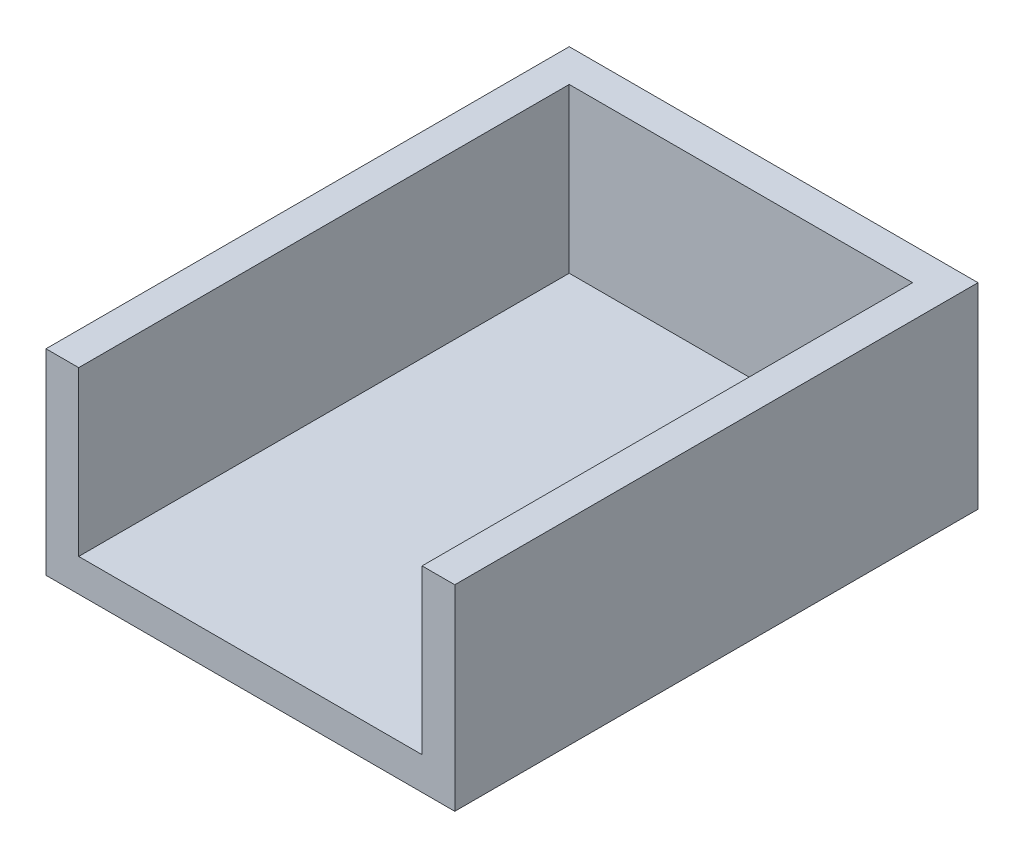
SolidWorks part; units mm, degrees
ref_plane "Front Plane" through (0, 0, 0) normal (0, 0, 1) x (1, 0, 0)
ref_plane "Top Plane" through (0, 0, 0) normal (0, 1, 0) x (1, 0, 0)
ref_plane "Right Plane" through (0, 0, 0) normal (1, 0, 0) x (0, 0, -1)
sketch "Sketch1" plane through (0, 0, 0) normal (0, 1, 0) x (1, 0, 0)
  line L1 (-62.5, -80) -> (62.5, -80)
  line L2 (-62.5, -80) -> (-62.5, 80)
  line L3 (-62.5, 80) -> (62.5, 80)
  line L4 (62.5, -80) -> (62.5, 80)
  line L5 (-62.5, -80) -> (62.5, 80) construction
  line L6 (-62.5, 80) -> (62.5, -80) construction
  point P0 (0, 0)
  dimension "D1" = 160
  dimension "D2" = 125
extrude "Boss-Extrude1" add sketch "Sketch1" along normal blind 60
shell "Shell1" thickness 10
sketch "Sketch2" plane through (0, 0, -80) normal (0, 0, -1) x (-1, 0, 0)
  line L0 (65.75, 53) -> (65.75, 3) construction
  line L1 (58.1499, 28.0001) -> (-53.2501, 28.0001)
  line L5 (65.75, 53) -> (65.75, 3) construction
  line L6 (-53.2501, 16.0001) -> (58.1499, 16.0001)
  line L7 (62.8337, 23.7501) -> (53.4662, 23.7501)
  line L8 (62.8337, 23.7501) -> (53.4662, 23.7501) construction
  line L9 (-48.5663, 23.7501) -> (-57.9338, 23.7501)
  line L10 (-48.5663, 23.7501) -> (-57.9338, 23.7501) construction
  arc A0 (53.4662, 23.7501) -> (62.8337, 23.7501) centre (58.1499, 22.0001) ccw
  arc A1 (53.4662, 23.7501) -> (62.8337, 23.7501) centre (58.1499, 22.0001) ccw construction
  arc A2 (-57.9338, 23.7501) -> (-48.5663, 23.7501) centre (-53.2501, 22.0001) ccw
  arc A3 (-57.9338, 23.7501) -> (-48.5663, 23.7501) centre (-53.2501, 22.0001) ccw construction
  arc A4 (-53.2501, 28.0001) -> (-53.2501, 16.0001) centre (-53.2501, 22.0001) ccw
  arc A5 (58.1499, 16.0001) -> (58.1499, 28.0001) centre (58.1499, 22.0001) ccw
  point P8 (58.1499, 16.005)
  point P12 (0, 0)
  dimension "D3" = 6
  dimension "D1" = 0
  dimension "D2" = 0
extrude "Cut-Extrude1" cut sketch "Sketch2" against normal blind 7
